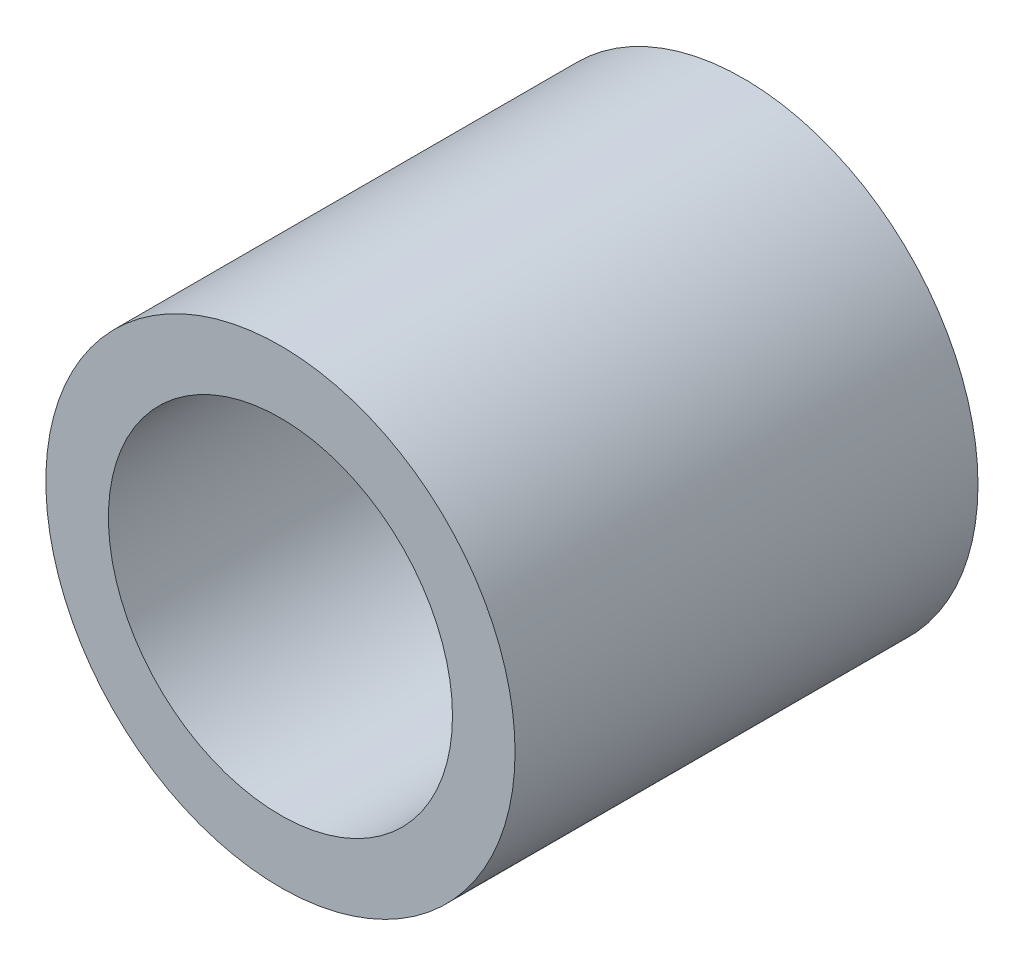
SolidWorks part; units mm, degrees
ref_plane "Alzado" through (0, 0, 0) normal (0, 0, 1) x (1, 0, 0)
ref_plane "Planta" through (0, 0, 0) normal (0, 1, 0) x (1, 0, 0)
ref_plane "Vista lateral" through (0, 0, 0) normal (1, 0, 0) x (0, 0, -1)
sketch "Croquis2" plane through (0, 0, 28.1) normal (0, 0, 1) x (1, 0, 0)
  circle A0 centre (-4.9763, -25.8) radius 11
  circle A1 centre (-4.9763, -25.8) radius 15
  dimension "D1" = 22
  dimension "D2" = 30
extrude "Saliente-Extruir1" add sketch "Croquis2" against normal blind 29.6
